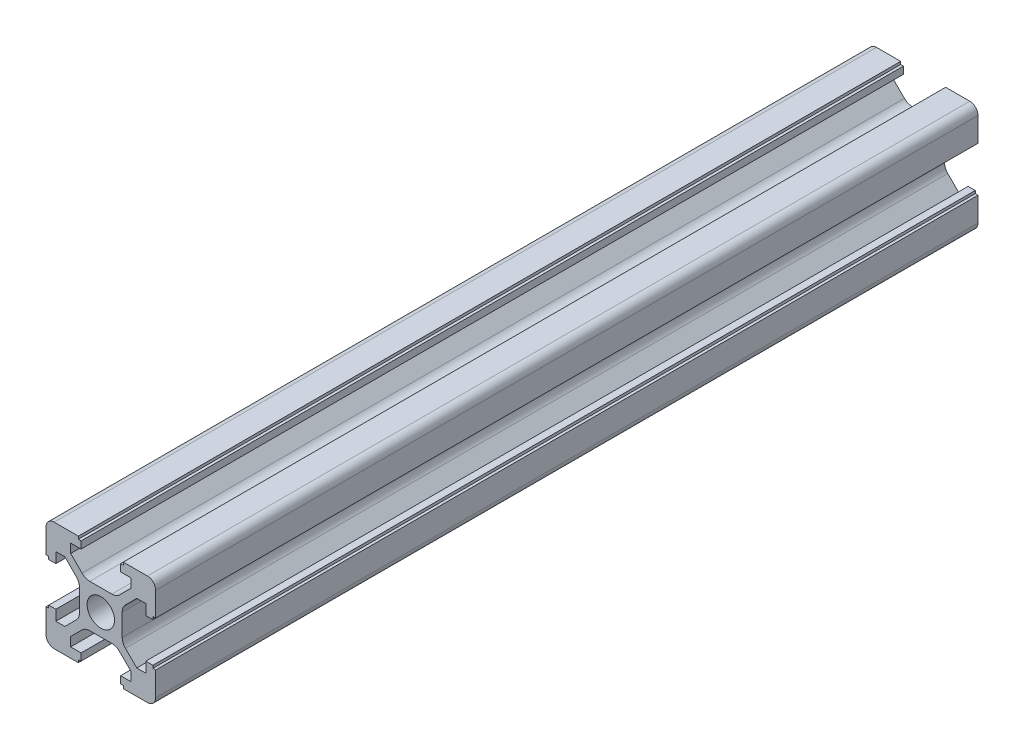
SolidWorks part; units mm, degrees
ref_plane "Front Plane" through (0, 0, 0) normal (0, 0, 1) x (1, 0, 0)
ref_plane "Top Plane" through (0, 0, 0) normal (0, 1, 0) x (1, 0, 0)
ref_plane "Right Plane" through (0, 0, 0) normal (1, 0, 0) x (0, 0, -1)
sketch "Sketch1" plane through (0, 0, 0) normal (0, 0, 1) x (1, 0, 0)
  line L0 (10, -4.1) -> (10, -8.5)
  line L1 (4.1, 10) -> (8.5, 10)
  line L2 (8.5, -10) -> (4.1, -10)
  line L3 (-8.5, -10) -> (-4.1, -10)
  line L4 (10, 8.5) -> (10, 4.1)
  line L7 (8.5, 10) -> (4.1, 10)
  line L8 (5.5, 6.5607) -> (3.4251, 4.4858)
  line L9 (8.5, 10) -> (4.1, 10)
  line L10 (3.9, 2.0109) -> (3.9, -2.0109)
  line L11 (2.0109, -3.9) -> (-2.0109, -3.9)
  line L12 (-3.9, -2.0109) -> (-3.9, 2.0109)
  line L13 (-2.0109, 3.9) -> (2.8393, 3.9)
  line L14 (2.5, 0) -> (22.2403, 0) construction
  line L15 (3.6, 9.5) -> (3.6, 8.2)
  line L16 (9.5, 3.6) -> (8.2, 3.6)
  line L17 (8.2, 3.6) -> (8.2, 5.5)
  line L18 (8.2, 5.5) -> (6.5607, 5.5)
  line L19 (10, -4.1) -> (10, -8.5)
  line L20 (4.1, 9.5) -> (3.6, 9.5)
  line L21 (4.1, 10) -> (4.1, 9.5)
  line L22 (8.5, 10) -> (4.1, 10)
  line L23 (10, 4.1) -> (9.5, 4.1)
  line L24 (9.5, 4.1) -> (9.5, 3.6)
  line L25 (5.5, 8.2) -> (5.5, 6.5607)
  line L26 (3.6, 8.2) -> (5.5, 8.2)
  line L27 (4.4858, 3.4251) -> (6.5607, 5.5)
  line L28 (10, -8.5) -> (10, -4.1)
  line L29 (6.5607, -5.5) -> (4.4858, -3.4251)
  line L30 (10, -8.5) -> (10, -4.1)
  line L31 (2.0109, -3.9) -> (-2.0109, -3.9)
  line L32 (3.9, 2.8393) -> (3.9, -2.0109)
  line L33 (9.5, -3.6) -> (8.2, -3.6)
  line L34 (3.6, -9.5) -> (3.6, -8.2)
  line L35 (3.6, -8.2) -> (5.5, -8.2)
  line L36 (5.5, -8.2) -> (5.5, -6.5607)
  line L37 (9.5, -4.1) -> (9.5, -3.6)
  line L38 (10, -4.1) -> (9.5, -4.1)
  line L39 (10, -8.5) -> (10, -4.1)
  line L40 (4.1, -10) -> (4.1, -9.5)
  line L41 (4.1, -9.5) -> (3.6, -9.5)
  line L42 (8.2, -5.5) -> (6.5607, -5.5)
  line L43 (8.2, -3.6) -> (8.2, -5.5)
  line L44 (3.4251, -4.4858) -> (5.5, -6.5607)
  line L45 (-4.1, -10) -> (-8.5, -10)
  line L46 (-10, -8.5) -> (-10, -4.1)
  line L47 (-8.5, -10) -> (-4.1, -10)
  line L48 (-5.5, -6.5607) -> (-3.4251, -4.4858)
  line L49 (-8.5, -10) -> (-4.1, -10)
  line L50 (-3.9, -2.0109) -> (-3.9, 2.0109)
  line L51 (2.0109, -3.9) -> (-2.0109, -3.9)
  line L52 (-3.6, -9.5) -> (-3.6, -8.2)
  line L53 (-9.5, -3.6) -> (-8.2, -3.6)
  line L54 (-8.2, -3.6) -> (-8.2, -5.5)
  line L55 (-8.2, -5.5) -> (-6.5607, -5.5)
  line L56 (-4.1, -9.5) -> (-3.6, -9.5)
  line L57 (-4.1, -10) -> (-4.1, -9.5)
  line L58 (-8.5, -10) -> (-4.1, -10)
  line L59 (-10, -4.1) -> (-9.5, -4.1)
  line L60 (-9.5, -4.1) -> (-9.5, -3.6)
  line L61 (-5.5, -8.2) -> (-5.5, -6.5607)
  line L62 (-3.6, -8.2) -> (-5.5, -8.2)
  line L63 (-4.4858, -3.4251) -> (-6.5607, -5.5)
  line L64 (-10, 4.1) -> (-10, 8.5)
  line L65 (-8.5, 10) -> (-4.1, 10)
  line L66 (-10, 8.5) -> (-10, 4.1)
  line L67 (-6.5607, 5.5) -> (-4.4858, 3.4251)
  line L68 (-10, 8.5) -> (-10, 4.1)
  line L69 (-2.0109, 3.9) -> (2.0109, 3.9)
  line L70 (-3.9, -2.0109) -> (-3.9, 2.0109)
  line L71 (-9.5, 3.6) -> (-8.2, 3.6)
  line L72 (-3.6, 9.5) -> (-3.6, 8.2)
  line L73 (-3.6, 8.2) -> (-5.5, 8.2)
  line L74 (-5.5, 8.2) -> (-5.5, 6.5607)
  line L75 (-9.5, 4.1) -> (-9.5, 3.6)
  line L76 (-10, 4.1) -> (-9.5, 4.1)
  line L77 (-10, 8.5) -> (-10, 4.1)
  line L78 (-4.1, 10) -> (-4.1, 9.5)
  line L79 (-4.1, 9.5) -> (-3.6, 9.5)
  line L80 (-8.2, 5.5) -> (-6.5607, 5.5)
  line L81 (-8.2, 3.6) -> (-8.2, 5.5)
  line L82 (-3.4251, 4.4858) -> (-5.5, 6.5607)
  line L83 (4.1, -10) -> (8.5, -10)
  arc A0 (2.0109, -3.9) -> (3.4251, -4.4858) centre (2.0109, -5.9) cw
  arc A1 (4.4858, -3.4251) -> (3.9, -2.0109) centre (5.9, -2.0109) cw
  arc A2 (3.9, 2.0109) -> (4.4858, 3.4251) centre (5.9, 2.0109) cw
  arc A3 (2.0109, 3.9) -> (3.4251, 4.4858) centre (2.0109, 5.9) ccw
  arc A4 (-2.0109, 3.9) -> (-3.4251, 4.4858) centre (-2.0109, 5.9) cw
  arc A5 (-4.4858, 3.4251) -> (-3.9, 2.0109) centre (-5.9, 2.0109) cw
  arc A6 (-3.4251, -4.4858) -> (-2.0109, -3.9) centre (-2.0109, -5.9) cw
  arc A7 (-3.9, -2.0109) -> (-4.4858, -3.4251) centre (-5.9, -2.0109) cw
  circle A8 centre (0, 0) radius 2.5
  arc A9 (-8.5, -10) -> (-10, -8.5) centre (-8.5, -8.5) cw
  arc A10 (-10, 8.5) -> (-8.5, 10) centre (-8.5, 8.5) cw
  arc A11 (8.5, 10) -> (10, 8.5) centre (8.5, 8.5) cw
  arc A12 (8.5, -10) -> (10, -8.5) centre (8.5, -8.5) ccw
  point P0 (0, 0)
  point P86 (0, 0)
  point P107 (10, -10)
  dimension "D3" = 2
  dimension "D5" = 5
  dimension "D2" = 1.5
  dimension "D8" = 1.5
  dimension "D4" = 6.1
  dimension "D6" = 20
  dimension "D7" = 6.1
  dimension "D9" = 20
  dimension "D11" = 0.5
  dimension "D12" = 0.5
extrude "Boss-Extrude2" add sketch "Sketch1" along normal blind 150
